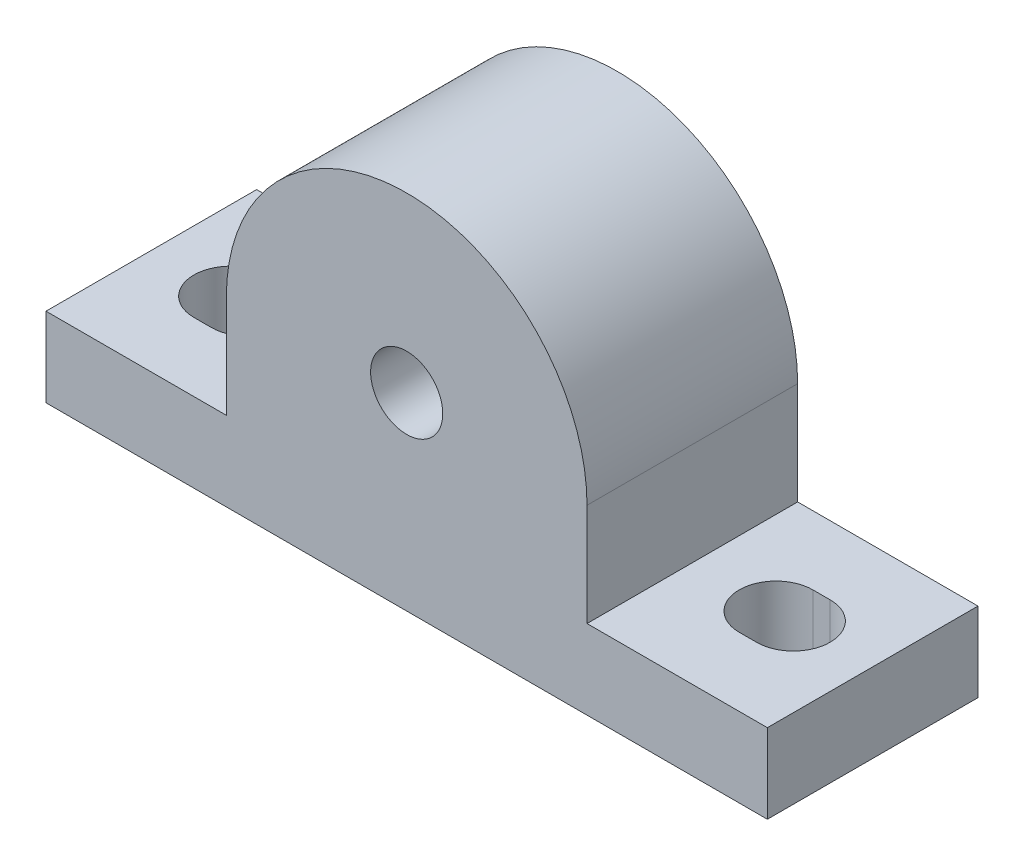
SolidWorks part; units mm, degrees
ref_plane "Front Plane" through (0, 0, 0) normal (0, 0, 1) x (1, 0, 0)
ref_plane "Top Plane" through (0, 0, 0) normal (0, 1, 0) x (1, 0, 0)
ref_plane "Right Plane" through (0, 0, 0) normal (1, 0, 0) x (0, 0, -1)
sketch "Sketch1" plane through (0, 0, 0) normal (0, 0, 1) x (1, 0, 0)
  line L0 (0, 0) -> (0, 31059.832) construction
  line L1 (0, 0) -> (31059.832, 0) construction
  line L2 (-63.5, -33.274) -> (63.5, -33.274)
  line L3 (-63.5, -33.274) -> (-63.5, -19.304)
  line L4 (-63.5, -19.304) -> (-31.75, -19.304)
  line L5 (63.5, -19.304) -> (63.5, -33.274)
  line L6 (31.75, -19.304) -> (63.5, -19.304)
  line L7 (-31.75, -1.27) -> (-31.75, -19.304)
  line L8 (31.75, -1.27) -> (31.75, -19.304)
  circle A0 centre (0, 0) radius 6.35
  arc A1 (-31.75, -1.27) -> (31.75, -1.27) centre (0, -1.27) cw
  point P10 (0, -33.274)
  point P15 (0, 30.48)
  dimension "D1" = 12.7
  dimension "D2" = 31.75
  dimension "D3" = 13.97
  dimension "D4" = 127
  dimension "D5" = 63.754
  dimension "D6" = 33.274
extrude "Boss-Extrude1" add sketch "Sketch1" along normal mid plane 37.084
sketch "Sketch2" plane through (0, -33.274, 0) normal (0, -1, 0) x (1, 0, 0)
  line L0 (-49.53, 0) -> (-46.482, 0) construction
  line L1 (-49.53, 6.477) -> (-46.482, 6.477)
  line L2 (-49.53, -6.477) -> (-46.482, -6.477)
  line L3 (0, 0) -> (0, 50000) construction
  line L4 (0, 0) -> (50000, 0) construction
  line L5 (49.53, 0) -> (46.482, 0) construction
  line L6 (49.53, 6.477) -> (46.482, 6.477)
  line L7 (49.53, -6.477) -> (46.482, -6.477)
  arc A0 (-49.53, 6.477) -> (-49.53, -6.477) centre (-49.53, 0) ccw
  arc A1 (-46.482, -6.477) -> (-46.482, 6.477) centre (-46.482, 0) ccw
  arc A2 (49.53, 6.477) -> (49.53, -6.477) centre (49.53, 0) cw
  arc A3 (46.482, -6.477) -> (46.482, 6.477) centre (46.482, 0) cw
  point P3 (-48.006, 0)
  point P8 (-56.007, 0)
  point P9 (-40.005, 0)
  point P16 (48.006, 0)
  dimension "D1" = 16.002
  dimension "D2" = 12.954
  dimension "D3" = 48.006
extrude "Cut-Extrude1" cut sketch "Sketch2" against normal through all
